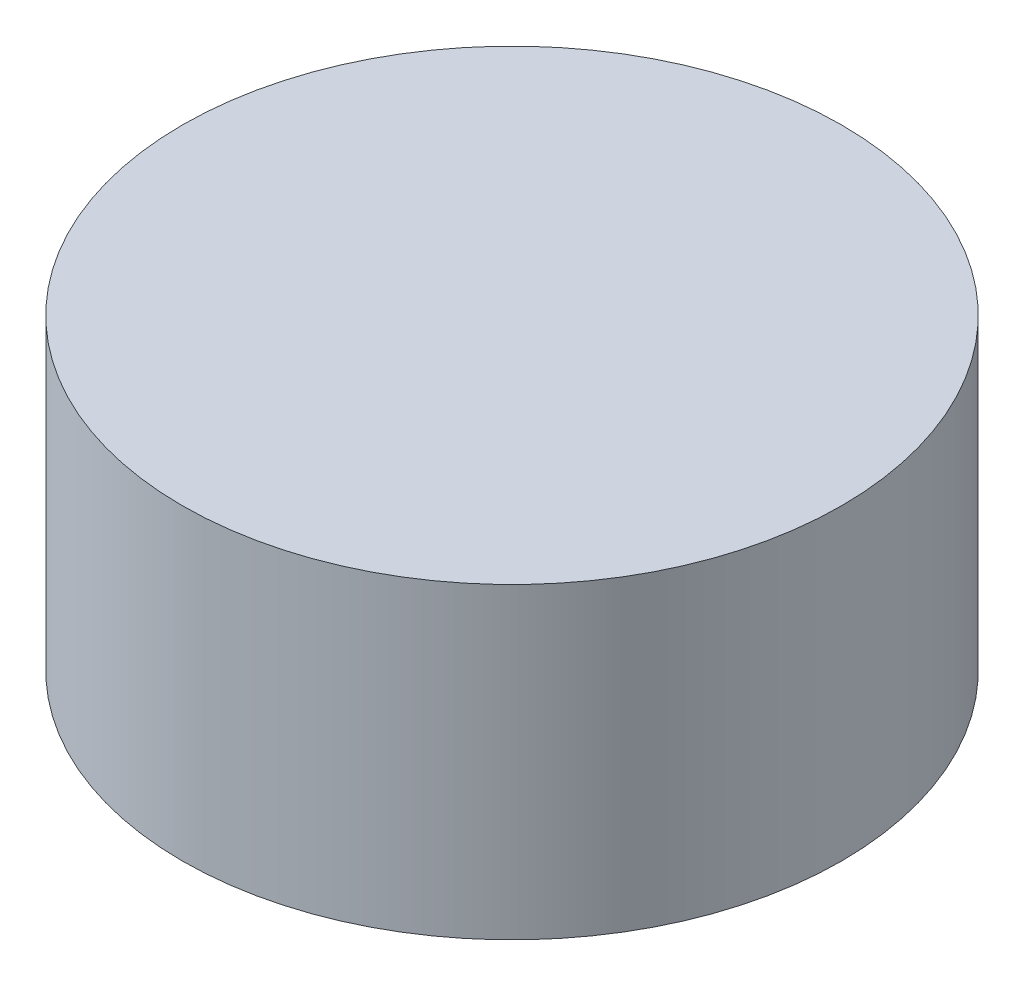
SolidWorks part; units mm, degrees
ref_plane "前视基准面" through (0, 0, 0) normal (0, 0, 1) x (1, 0, 0)
ref_plane "上视基准面" through (0, 0, 0) normal (0, 1, 0) x (1, 0, 0)
ref_plane "右视基准面" through (0, 0, 0) normal (1, 0, 0) x (0, 0, -1)
sketch "草图1" plane through (0, 0, 0) normal (0, 1, 0) x (1, 0, 0)
  circle A0 centre (0, 0) radius 75
  point P3 (0, 0)
  dimension "D1" = 150
extrude "凸台-拉伸1" add sketch "草图1" along normal blind 70
ref_plane "基准面1" through (0, 0, 0) normal (0, 0, 1) x (1, 0, 0)
ref_plane "基准面2" through (0, 0, 0) normal (1, 0, 0) x (0, 0, -1)
